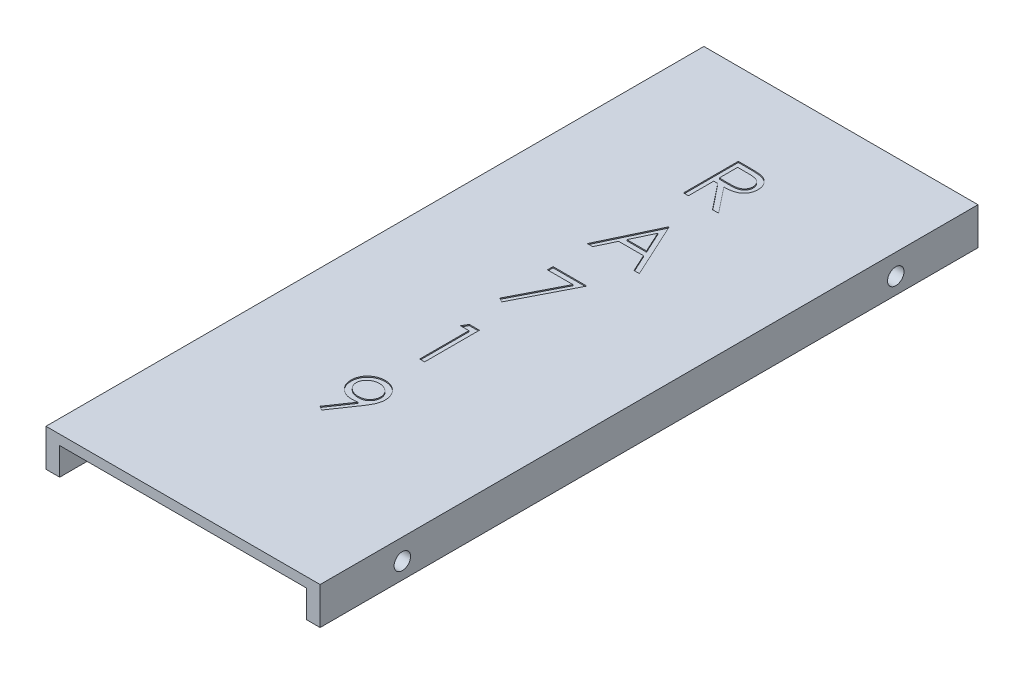
SolidWorks part; units mm, degrees
material "Cedar"
ref_plane "Front Plane" through (0, 0, 0) normal (0, 0, 1) x (1, 0, 0)
ref_plane "Top Plane" through (0, 0, 0) normal (0, 1, 0) x (1, 0, 0)
ref_plane "Right Plane" through (0, 0, 0) normal (1, 0, 0) x (0, 0, -1)
sketch "Sketch2" plane through (0, 0, 0) normal (0, 0, 1) x (1, 0, 0)
  line L0 (0, 0) -> (0, 68)
  line L1 (0, 68) -> (500, 68)
  line L2 (0, 0) -> (25, 0)
  line L3 (25, 50) -> (475, 50)
  line L4 (25, 50) -> (25, 0)
  line L5 (500, 68) -> (500, 0)
  line L6 (500, 0) -> (475, 0)
  line L7 (475, 0) -> (475, 50)
  point P7 (0, 0)
  point P11 (0, 0)
  point P12 (0, 0)
  point P13 (0, 0)
  dimension "D1" = 68
  dimension "D2" = 500
  dimension "D3" = 25
  dimension "D4" = 50
  dimension "D5" = 68
  dimension "D6" = 25
  dimension "D7" = 50
extrude "Boss-Extrude1" add sketch "Sketch2" along normal blind 1200
sketch "Sketch3" plane through (500, 0, 0) normal (1, 0, 0) x (0, 0, -1)
  line L1 (-1200, 0) -> (0, 0) construction
  line L2 (-1200, 0) -> (-1200, 68) construction
  line L3 (0, 0) -> (0, 68) construction
  circle A0 centre (-1050, 30) radius 15
  circle A1 centre (-150, 30) radius 15
  dimension "D1" = 30
  dimension "D3" = 30
  dimension "D4" = 30
  dimension "D2" = 150
  dimension "D5" = 150
  dimension "D6" = 30
extrude "Cut-Extrude1" cut sketch "Sketch3" against normal through all
sketch "Sketch4" plane through (0, 68, 0) normal (0, 1, 0) x (1, 0, 0)
  line L0 (0, -1200) -> (0, 0) construction
  line L1 (500, 0) -> (0, 0) construction
  text T0 "R\r\nA\r\n7\r\n1\r\n9" font "Century Gothic" height 100
  dimension "D1" = 200
  dimension "D2" = 250
extrude "Cut-Extrude2" cut sketch "Sketch4" against normal blind 2
sketch "Sketch5" plane through (0, 50, 0) normal (0, -1, 0) x (1, 0, 0)
  line L0 (0, 1200) -> (0, 0) construction
  line L1 (25, 1200) -> (475, 1200) construction
  text T0 "R\r\nA\r\n7\r\n1\r\n9" font "Century Gothic" height 100
  dimension "D1" = 200
  dimension "D2" = 250
extrude "Cut-Extrude3" cut sketch "Sketch5" against normal blind 2
